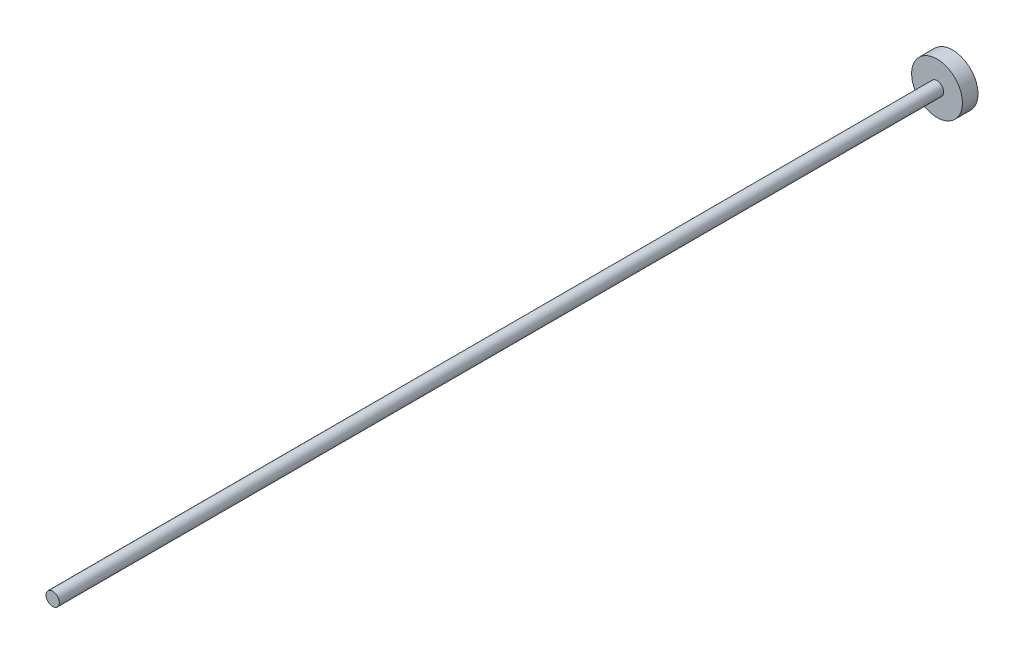
SolidWorks part; units mm, degrees
ref_plane "Front Plane" through (0, 0, 0) normal (0, 0, 1) x (1, 0, 0)
ref_plane "Top Plane" through (0, 0, 0) normal (0, 1, 0) x (1, 0, 0)
ref_plane "Right Plane" through (0, 0, 0) normal (1, 0, 0) x (0, 0, -1)
sketch "Sketch1" plane through (0, 0, 0) normal (0, 0, 1) x (1, 0, 0)
  circle A0 centre (0, 0) radius 2.44
  dimension "D1" = 4.88
extrude "Boss-Extrude1" add sketch "Sketch1" along normal blind 1.5
sketch "Sketch2" plane through (0, 0, 1.5) normal (0, 0, 1) x (1, 0, 0)
  circle A0 centre (0, 0) radius 0.64
  dimension "D1" = 1.28
extrude "Boss-Extrude2" add sketch "Sketch2" along normal blind 85
